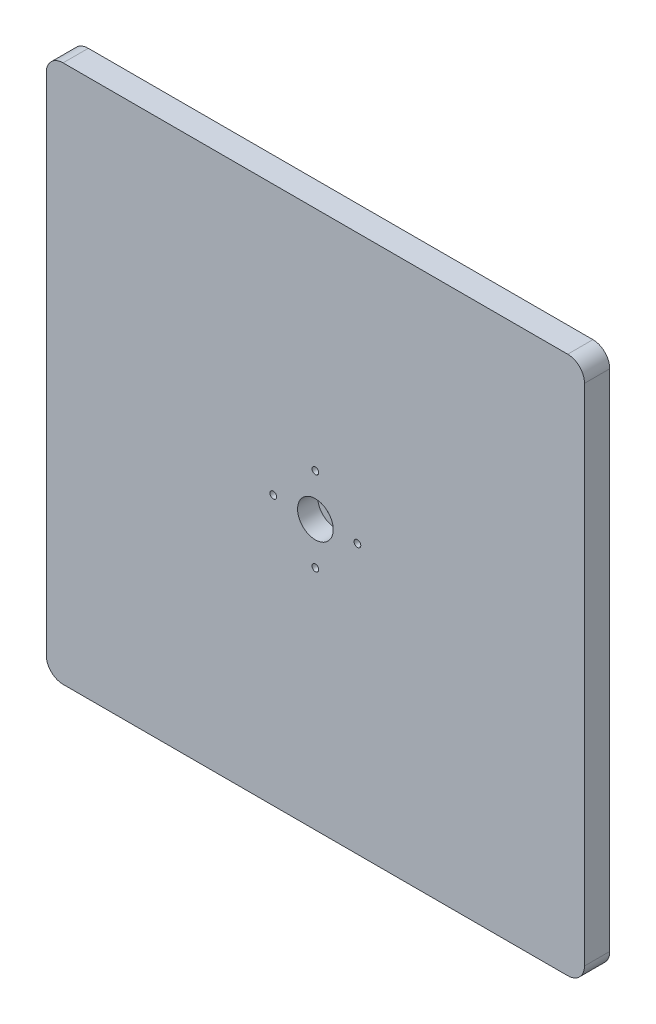
SolidWorks part; units mm, degrees
material "Cedar"
ref_plane "Plan de face" through (0, 0, 0) normal (0, 0, 1) x (1, 0, 0)
ref_plane "Plan de dessus" through (0, 0, 0) normal (0, 1, 0) x (1, 0, 0)
ref_plane "Plan de droite" through (0, 0, 0) normal (1, 0, 0) x (0, 0, -1)
sketch "Sketch1" plane through (0, 0, 0) normal (0, 0, 1) x (1, 0, 0)
  line L1 (-150, 160) -> (150, 160)
  line L2 (-160, 150) -> (-160, -150)
  line L3 (-150, -160) -> (150, -160)
  line L4 (160, 150) -> (160, -150)
  line L5 (-160, 160) -> (160, -160) construction
  line L6 (-160, -160) -> (160, 160) construction
  arc A0 (-160, -150) -> (-150, -160) centre (-150, -150) ccw
  arc A1 (150, -160) -> (160, -150) centre (150, -150) ccw
  arc A2 (150, 160) -> (160, 150) centre (150, 150) cw
  arc A3 (-150, 160) -> (-160, 150) centre (-150, 150) ccw
  point P0 (0, 0)
  dimension "D2" = 10
  dimension "D1" = 320
extrude "Boss-Extrude1" add sketch "Sketch1" along normal blind 15
sketch "Sketch2" plane through (0, 0, 15) normal (0, 0, 1) x (1, 0, 0)
  circle A0 centre (0, 0) radius 10.6
  dimension "D1" = 21.2
extrude "Cut-Extrude1" cut sketch "Sketch2" against normal blind 12
sketch "Sketch3" plane through (0, 0, 3) normal (0, 0, 1) x (1, 0, 0)
  circle A0 centre (0, 0) radius 6.5
  dimension "D1" = 13
extrude "Cut-Extrude2" cut sketch "Sketch3" against normal blind 10
sketch "Sketch4" plane through (0, 0, 15) normal (0, 0, 1) x (1, 0, 0)
  circle A0 centre (0, 25) radius 2
  circle A1 centre (25, 0) radius 2
  circle A2 centre (0, -25) radius 2
  circle A3 centre (-25, 0) radius 2
  dimension "D5" = 4
  dimension "D1" = 25
  dimension "D2" = 25
  dimension "D3" = 25
  dimension "D4" = 25
extrude "Cut-Extrude3" cut sketch "Sketch4" against normal blind 15
